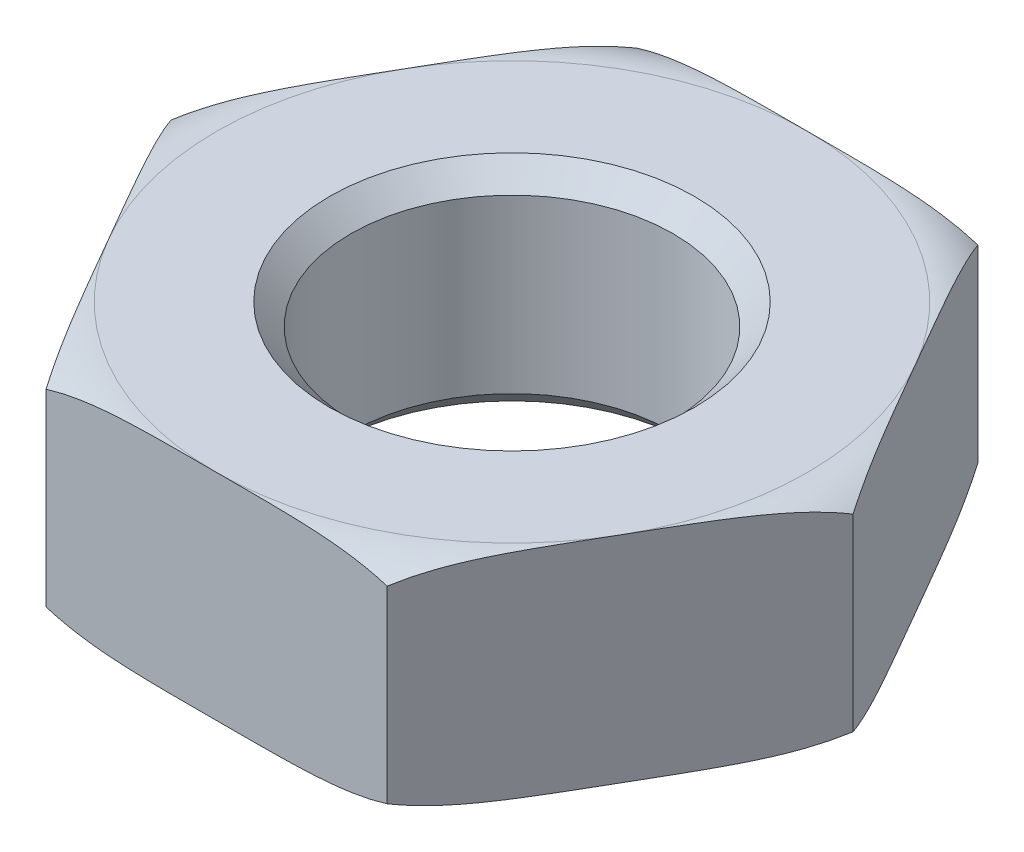
SolidWorks part; units mm, degrees
ref_plane "Front Plane" through (0, 0, 0) normal (0, 0, 1) x (1, 0, 0)
ref_plane "Top Plane" through (0, 0, 0) normal (0, 1, 0) x (1, 0, 0)
ref_plane "Right Plane" through (0, 0, 0) normal (1, 0, 0) x (0, 0, -1)
sketch "Sketch1" plane through (0, 0, 0) normal (0, 1, 0) x (1, 0, 0)
  line L1 (3.1754, 0) -> (1.5877, 2.75)
  line L2 (1.5877, 2.75) -> (-1.5877, 2.75)
  line L3 (-1.5877, 2.75) -> (-3.1754, 0)
  line L4 (-3.1754, 0) -> (-1.5877, -2.75)
  line L5 (-1.5877, -2.75) -> (1.5877, -2.75)
  line L6 (1.5877, -2.75) -> (3.1754, 0)
  circle A0 centre (0, 0) radius 2.75 construction
  circle A1 centre (0, 0) radius 1.5
  dimension "D1" = 3
  dimension "D2" = 5.5
extrude "Boss-Extrude1" add sketch "Sketch1" along normal mid plane 2
sketch "Sketch2" plane through (0, 0, 0) normal (0, 0, 1) x (1, 0, 0)
  line L1 (0, -1) -> (-3.1754, -1) construction
  line L2 (-1.5877, -1) -> (1.5877, -1) construction
  line L3 (-2.75, -1) -> (-2.75, 0) construction
  line L4 (-3.55, -0.2) -> (-3.55, -1)
  line L5 (-3.55, -1) -> (-2.75, -1)
  line L6 (0, 0) -> (0, 4.8499) construction
  arc A0 (-2.75, -1) -> (-3.55, -0.2) centre (-2.75, -0.2) cw
  dimension "D1" = 0.8
  dimension "D2" = 0.8
revolve "Cut-Revolve1" cut sketch "Sketch2" angle 360 about L6
mirror "Mirror2" about plane through (0, 0, 0) normal (0, 1, 0) of "Cut-Revolve1"
chamfer "Chamfer1" distance 0.2 angle 45 2 edges at (0, -1, 1.5) (0, 1, 1.5)
equation "\"D2@Sketch2\"=\"D1@Sketch2\""
